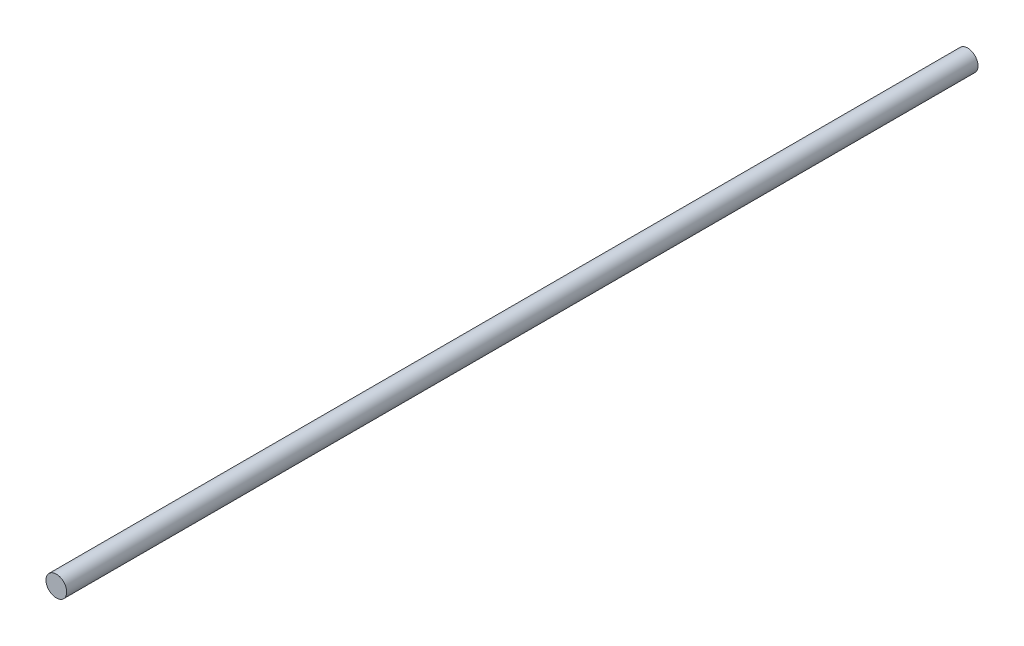
SolidWorks part; units mm, degrees
ref_plane "Plan de face" through (0, 0, 0) normal (0, 0, 1) x (1, 0, 0)
ref_plane "Plan de dessus" through (0, 0, 0) normal (0, 1, 0) x (1, 0, 0)
ref_plane "Plan de droite" through (0, 0, 0) normal (1, 0, 0) x (0, 0, -1)
sketch "Esquisse1" plane through (0, 0, 0) normal (0, 0, 1) x (1, 0, 0)
  circle A0 centre (0, 0) radius 3
extrude "Extrusion1" add sketch "Esquisse1" along normal blind 264
